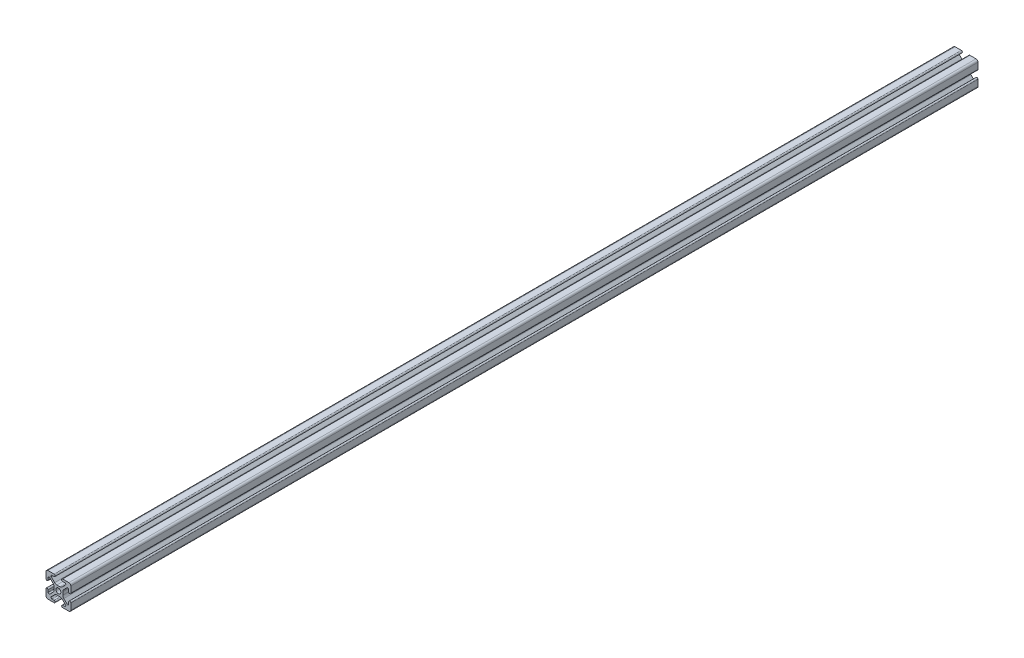
SolidWorks part; units mm, degrees
material "6005A-T61"
ref_plane "Front Plane" through (0, 0, 0) normal (0, 0, 1) x (1, 0, 0)
ref_plane "Top Plane" through (0, 0, 0) normal (0, 1, 0) x (1, 0, 0)
ref_plane "Right Plane" through (0, 0, 0) normal (1, 0, 0) x (0, 0, -1)
sketch "Sketch1" plane through (0, 0, 0) normal (0, 0, 1) x (1, 0, 0)
  line L0 (-8.6363, 7.1116) -> (-5.4322, 3.9121)
  line L1 (-4.455, 1.5554) -> (-4.455, -1.5554)
  line L2 (-5.4322, -3.9121) -> (-8.6363, -7.1116)
  line L3 (-10.36, -6.3969) -> (-10.36, -4.32)
  line L4 (-12.5, -4.32) -> (-12.5, -8.6518)
  line L5 (-12.5, -8.6518) -> (-12.5, -10.5371)
  line L6 (-10.5371, -12.5) -> (-8.4416, -12.5)
  line L7 (-8.4416, -12.5) -> (-4.3879, -12.5)
  line L8 (-4.3879, -10.36) -> (-6.42, -10.36)
  line L9 (-7.1337, -8.6353) -> (-3.7953, -5.3018)
  line L10 (-1.5554, -4.375) -> (1.5554, -4.375)
  line L11 (10.36, 4.32) -> (10.36, 6.3969)
  line L12 (12.5, 7.9913) -> (12.5, 4.32)
  line L13 (12.5, 10.5371) -> (12.5, 7.9913)
  line L14 (4.32, 12.5) -> (10.5371, 12.5)
  line L16 (6.42, 10.36) -> (4.32, 10.36)
  line L17 (3.7953, 5.3018) -> (7.1337, 8.6353)
  line L18 (7.1337, -8.6353) -> (3.7953, -5.3018)
  line L19 (4.3879, -10.36) -> (6.42, -10.36)
  line L20 (8.4416, -12.5) -> (4.3879, -12.5)
  line L21 (10.5371, -12.5) -> (8.4416, -12.5)
  line L22 (12.5, -8.6518) -> (12.5, -10.5371)
  line L23 (12.5, -4.32) -> (12.5, -8.6518)
  line L24 (10.36, -6.3969) -> (10.36, -4.32)
  line L25 (5.4322, -3.9121) -> (8.6363, -7.1116)
  line L26 (4.455, 1.5554) -> (4.455, -1.5554)
  line L27 (8.6363, 7.1116) -> (5.4322, 3.9121)
  line L28 (1.5554, 4.375) -> (-1.5554, 4.375)
  line L29 (-3.7953, 5.3018) -> (-7.1337, 8.6353)
  line L30 (-6.42, 10.36) -> (-4.32, 10.36)
  line L32 (-4.32, 12.5) -> (-10.5371, 12.5)
  line L33 (-12.5, 10.5371) -> (-12.5, 7.9913)
  line L34 (-12.5, 7.9913) -> (-12.5, 4.32)
  line L35 (-10.36, 4.32) -> (-10.36, 6.3969)
  line L36 (-15.7693, 0) -> (12.5, 0) construction
  line L37 (0, 13.9334) -> (0, -12.3541) construction
  circle A0 centre (0, 0) radius 2.5
  arc A1 (-8.6363, 7.1116) -> (-10.36, 6.3969) centre (-9.35, 6.3969) ccw
  arc A2 (-4.455, 1.5554) -> (-5.4322, 3.9121) centre (-7.7855, 1.5554) ccw
  arc A3 (-5.4322, -3.9121) -> (-4.455, -1.5554) centre (-7.7855, -1.5554) ccw
  arc A4 (-10.36, -6.3969) -> (-8.6363, -7.1116) centre (-9.35, -6.3969) ccw
  arc A5 (-10.36, -4.32) -> (-12.5, -4.32) centre (-11.43, -4.32) ccw
  arc A6 (-12.5, -10.5371) -> (-10.5371, -12.5) centre (-10.5371, -10.5371) ccw
  arc A7 (-4.3879, -12.5) -> (-4.3879, -10.36) centre (-4.3879, -11.43) ccw
  arc A8 (-7.1337, -8.6353) -> (-6.42, -10.36) centre (-6.42, -9.35) ccw
  arc A9 (-1.5554, -4.375) -> (-3.7953, -5.3018) centre (-1.5554, -7.545) ccw
  arc A10 (12.5, 4.32) -> (10.36, 4.32) centre (11.43, 4.32) cw
  arc A11 (10.5371, 12.5) -> (12.5, 10.5371) centre (10.5371, 10.5371) cw
  arc A12 (4.32, 10.36) -> (4.32, 12.5) centre (4.32, 11.43) cw
  arc A13 (6.42, 10.36) -> (7.1337, 8.6353) centre (6.42, 9.35) cw
  arc A14 (3.7953, 5.3018) -> (1.5554, 4.375) centre (1.5554, 7.545) cw
  arc A15 (1.5554, -4.375) -> (3.7953, -5.3018) centre (1.5554, -7.545) cw
  arc A16 (7.1337, -8.6353) -> (6.42, -10.36) centre (6.42, -9.35) cw
  arc A17 (4.3879, -12.5) -> (4.3879, -10.36) centre (4.3879, -11.43) cw
  arc A18 (12.5, -10.5371) -> (10.5371, -12.5) centre (10.5371, -10.5371) cw
  arc A19 (10.36, -4.32) -> (12.5, -4.32) centre (11.43, -4.32) cw
  arc A20 (10.36, -6.3969) -> (8.6363, -7.1116) centre (9.35, -6.3969) cw
  arc A21 (5.4322, -3.9121) -> (4.455, -1.5554) centre (7.7855, -1.5554) cw
  arc A22 (4.455, 1.5554) -> (5.4322, 3.9121) centre (7.7855, 1.5554) cw
  arc A23 (8.6363, 7.1116) -> (10.36, 6.3969) centre (9.35, 6.3969) cw
  arc A24 (-3.7953, 5.3018) -> (-1.5554, 4.375) centre (-1.5554, 7.545) ccw
  arc A25 (-6.42, 10.36) -> (-7.1337, 8.6353) centre (-6.42, 9.35) ccw
  arc A26 (-4.32, 10.36) -> (-4.32, 12.5) centre (-4.32, 11.43) ccw
  arc A27 (-10.5371, 12.5) -> (-12.5, 10.5371) centre (-10.5371, 10.5371) ccw
  arc A28 (-12.5, 4.32) -> (-10.36, 4.32) centre (-11.43, 4.32) ccw
  dimension "D4" = 14.86
  dimension "D5" = 2.14
  dimension "D6" = 6.5
  dimension "D7" = 8.75
  dimension "D8" = 1.01
  dimension "D9" = 3.17
  dimension "D14" = 5
  dimension "D1" = 25
  dimension "D2" = 8.91
  dimension "D3" = 12.5
  dimension "D12" = 2.14
extrude "Extrude1" add sketch "Sketch1" against normal blind 914.4
equation "\"WallThickness\"= 0.5cm"
equation "\"BottomPlateX\"= 3ft"
equation "\"BottomPlateZ\"= 2ft"
equation "\"BottomPlateHoleD\"=((\"ArmPlateX\")^2+(\"ArmPlateDepth\")^2)^.5+ 10mm"
equation "\"ActuatorPinD\"= 6.35mm"
equation "\"ActuatorPinL\"= 15cm"
equation "\"Box-X\"= 40cm"
equation "\"Box-Z\"= 20cm"
equation "\"Box-Y\"= 30cm"
equation "\"ArmPlateThickness\"= .125in"
equation "\"ArmPlateX\"= 18in"
equation "\"ArmPlateDepth\"= 7.1875in"
equation "\"DCMotor1D\"= 65mm"
equation "\"DCMotor1L\"= 215mm"
equation "\"DCMotor1ShaftL\"= 30mm"
equation "\"DCMotor2X\"= 68mm"
equation "\"DCMotor2D\"= 65mm"
equation "\"DCMotor2L\"= 208mm"
equation "\"DCMotor2ShaftL\"= 39mm"
equation "\"DCMotor2ShaftD\"= 15mm"
equation "\"BenchDepth\"= 5cm"
equation "\"BenchH\"= 10cm"
equation "\"BenchL\"= 15cm"
equation "\"PillowBlockW\"= 5cm"
equation "\"PillowBlockCenterH\"= \"DCMotor2X\"/2"
equation "\"EncoderRadius\"= 19mm"
equation "\"EncoderShaftL\"= 15mm"
equation "\"EncoderL\"= 33mm"
equation "\"EncoderHousingThickness\"= 7.5mm"
equation "\"TurntableID\"= 70mm"
equation "\"TurntableInner2*t\" = (\"TurntableOD\"-\"TurntableID\")*.25 - 1mm"
equation "\"TurntableInnerHoleRadius\"= \"TurntableID\"*.5 + \"TurntableInner2*t\"*.5"
equation "\"TurntableOD\"= 120mm"
equation "\"TurntableOuterHoleRadius\" = \"TurntableOD\"*.5 - ((\"TurntableOD\"-\"TurntableID\")*.25-.5mm)*.5"
equation "\"4040Height\"= 30cm"
equation "\"LENGTH@Extrude1\"=\"BottomPlateX\""
